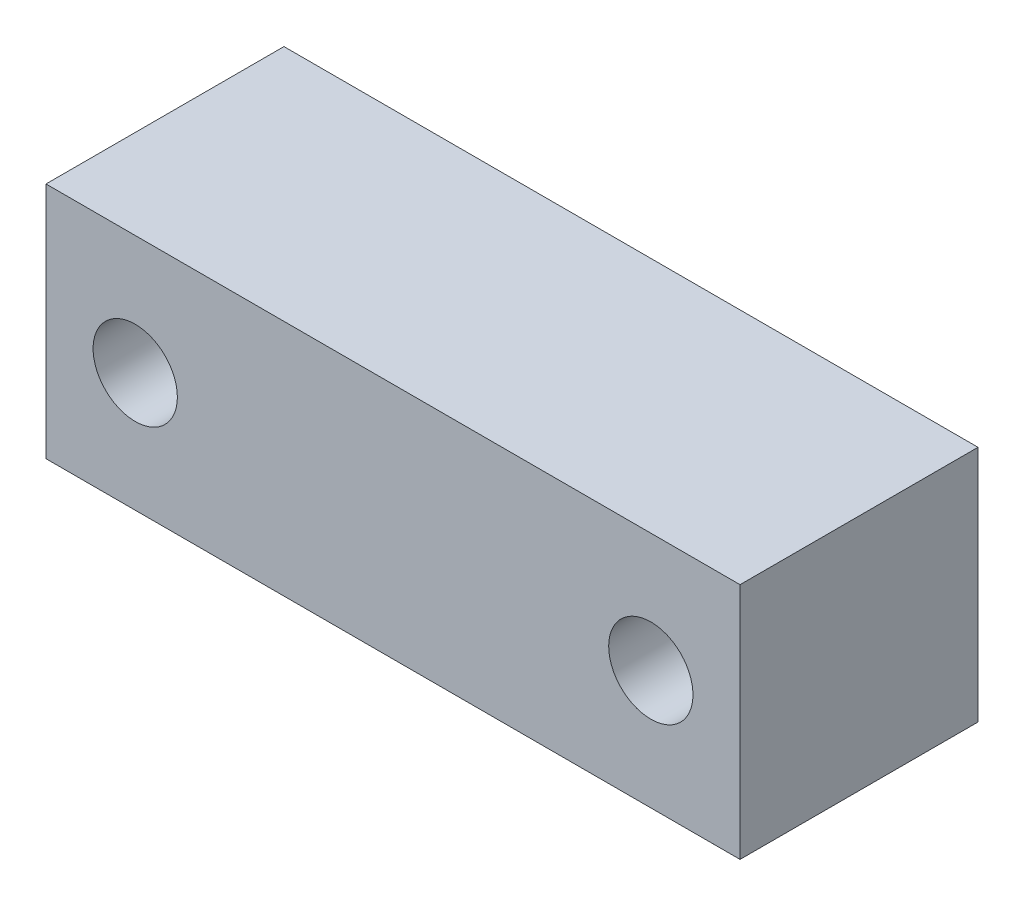
SolidWorks part; units mm, degrees
material "SKD11淬火HRC56-60"
ref_plane "前基準面" through (0, 0, 0) normal (0, 0, 1) x (1, 0, 0)
ref_plane "上基準面" through (0, 0, 0) normal (0, 1, 0) x (1, 0, 0)
ref_plane "右基準面" through (0, 0, 0) normal (1, 0, 0) x (0, 0, -1)
sketch "草图1" plane through (0, 0, 0) normal (0, 0, 1) x (1, 0, 0)
  line L1 (0, 0) -> (70, 0)
  line L2 (0, 0) -> (0, 24)
  line L3 (0, 24) -> (70, 24)
  line L4 (70, 0) -> (70, 24)
  dimension "D1" = 24
  dimension "D2" = 70
extrude "凸台-拉伸1" add sketch "草图1" along normal blind 24
sketch "草图2" plane through (0, 0, 24) normal (0, 0, 1) x (1, 0, 0)
  line L0 (35, 0) -> (35, 24) construction
  line L1 (0, 0) -> (70, 0) construction
  line L2 (70, 24) -> (0, 24) construction
  line L3 (0, 12) -> (70, 12) construction
  line L4 (0, 24) -> (0, 0) construction
  line L5 (70, 0) -> (70, 24) construction
  circle A0 centre (9, 12) radius 4.25
  circle A1 centre (61, 12) radius 4.25
  dimension "D1" = 52
  dimension "D2" = 8.5
extrude "切除-拉伸1" cut sketch "草图2" against normal through all
